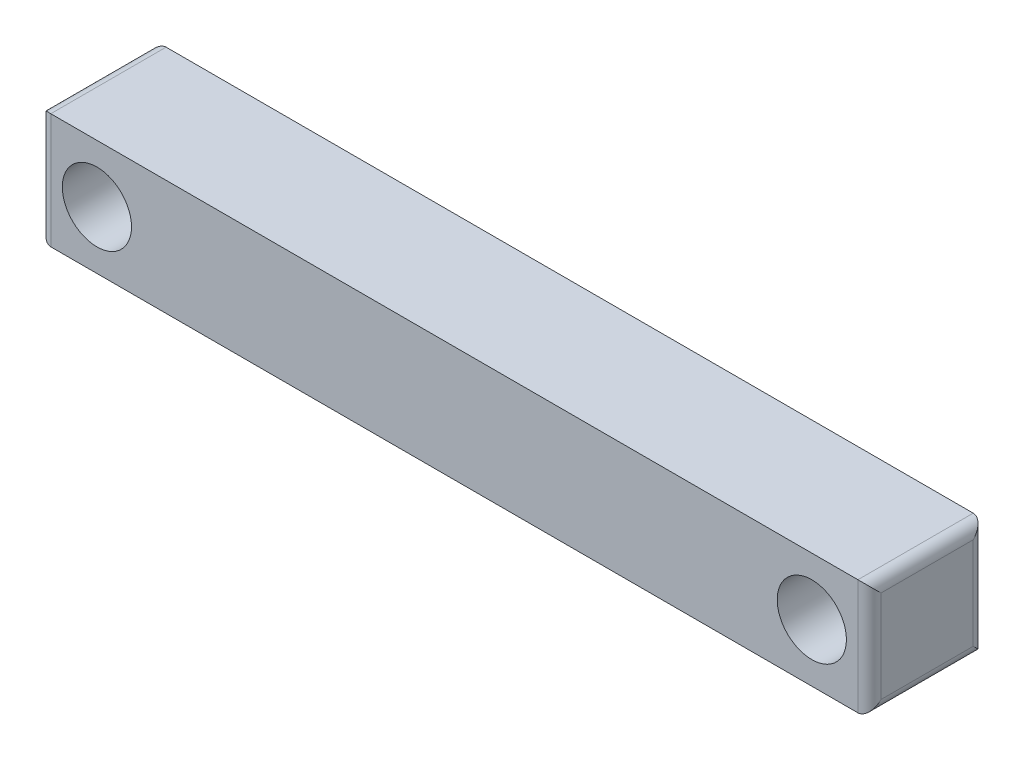
SolidWorks part; units mm, degrees
ref_plane "Front Plane" through (0, 0, 0) normal (0, 0, 1) x (1, 0, 0)
ref_plane "Top Plane" through (0, 0, 0) normal (0, 1, 0) x (1, 0, 0)
ref_plane "Right Plane" through (0, 0, 0) normal (1, 0, 0) x (0, 0, -1)
sketch "Sketch1" plane through (0, 0, 0) normal (0, 0, 1) x (1, 0, 0)
  line L1 (-78.884, 85.5389) -> (101.116, 85.5389)
  line L2 (-78.884, 85.5389) -> (-78.884, 60.5389)
  line L3 (-78.884, 60.5389) -> (101.116, 60.5389)
  line L4 (101.116, 85.5389) -> (101.116, 60.5389)
  circle A0 centre (-66.384, 73.0389) radius 7.5
  circle A1 centre (88.616, 73.0389) radius 7.5
  dimension "D3" = 15
  dimension "D6" = 15
  dimension "D1" = 180
  dimension "D2" = 25
  dimension "D4" = 12.5
  dimension "D5" = 12.5
  dimension "D7" = 12.5
  dimension "D8" = 12.5
extrude "Boss-Extrude1" add sketch "Sketch1" along normal blind 25
fillet "Fillet1" radius 2.5 4 edges at (-78.884, 85.5389, 12.5) (-78.884, 73.0389, 25) (-78.884, 60.5389, 12.5) (-78.884, 73.0389, 0)
fillet "Fillet2" radius 2.5 4 edges at (101.116, 60.5389, 12.5) (101.116, 73.0389, 25) (101.116, 85.5389, 12.5) (101.116, 73.0389, 0)
